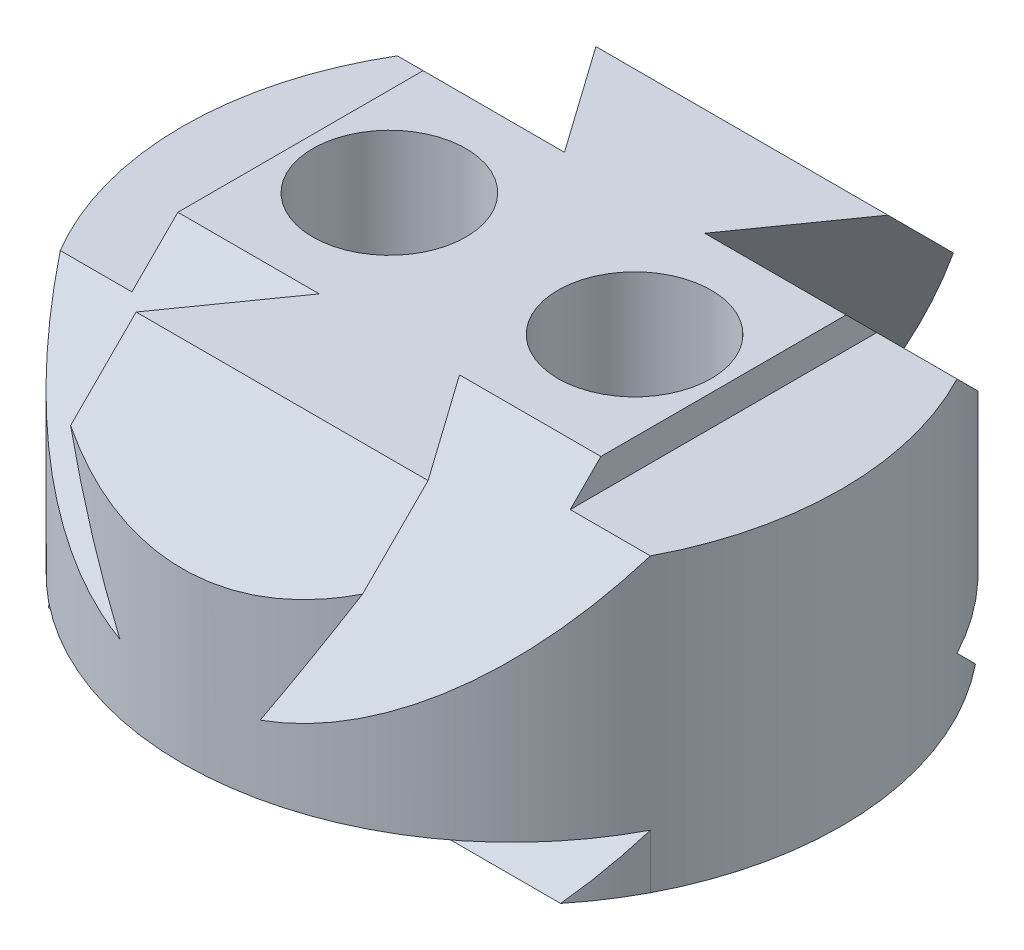
SolidWorks part; units mm, degrees
ref_plane "Front Plane" through (0, 0, 0) normal (0, 0, 1) x (1, 0, 0)
ref_plane "Top Plane" through (0, 0, 0) normal (0, 1, 0) x (1, 0, 0)
ref_plane "Right Plane" through (0, 0, 0) normal (1, 0, 0) x (0, 0, -1)
sketch "Sketch1" plane through (0, 0, 0) normal (0, 1, 0) x (1, 0, 0)
  circle A0 centre (0, 0) radius 21.5
  dimension "D1" = 43
extrude "Boss-Extrude1" add sketch "Sketch1" against normal blind 4
sketch "Sketch2" plane through (0, 0, 0) normal (0, 1, 0) x (1, 0, 0)
  circle A0 centre (0, 0) radius 5.875
  dimension "D1" = 11.75
extrude "Boss-Extrude2" add sketch "Sketch2" along normal blind 65
sketch "Sketch3" plane through (0, 0, 0) normal (0, 1, 0) x (1, 0, 0)
  line L0 (0, 0) -> (0, 21.5) construction
  line L1 (0, 21.5) -> (0, -21.5) construction
  circle A0 centre (0, 0) radius 21.5 construction
ref_plane "Plane1" through (0, 15.5, 0) normal (0, 1, 0) x (1, 0, 0)
sketch "Sketch5" plane through (0, 0, 0) normal (1, 0, 0) x (0, 0, -1)
  line L4 (21.5, 0) -> (-21.5, 0) construction
  line L5 (6, 0) -> (0, 0) construction
  line L8 (21.5, 0) -> (0, 0)
  line L10 (-21.5, 0) -> (0, 0)
  line L11 (21.5, 0) -> (6, 15.5)
  line L12 (23.65, 15.5) -> (-23.65, 15.5) construction
  line L13 (6, 15.5) -> (-6, 15.5)
  line L14 (-6, 15.5) -> (-21.5, 0)
  dimension "D1" = 21.5
  dimension "D2" = 15.5
  dimension "D3" = 15.5
extrude "Boss-Extrude3" add sketch "Sketch5" along normal up to surface and the other way up to surface up to face at (0, -4, 21.5) other way up to face at (0, -4, 21.5)
ref_plane "Plane2" through (0, 4.75, -4.75) normal (0, 0.7071, -0.7071) x (-1, 0, 0)
ref_plane "Plane3" through (0, 4.75, 4.75) normal (0, -0.7071, -0.7071) x (-1, 0, 0)
sketch "Sketch6" plane through (0, 4.75, 4.75) normal (0, -0.7071, -0.7071) x (-1, 0, 0)
  line L0 (0, 15.2028) -> (4.5753, 15.2028)
  line L1 (20.6458, 15.2028) -> (-20.6458, 15.2028) construction
  line L2 (4.5753, 15.2028) -> (9.525, 20.1525)
  line L3 (9.525, 20.1525) -> (0, 20.1525)
  line L4 (0, 20.1525) -> (-9.525, 20.1525)
  line L5 (-9.525, 20.1525) -> (-4.5753, 15.2028)
  line L6 (-4.5753, 15.2028) -> (0, 15.2028)
  dimension "D1" = 7
  dimension "D2" = 45
  dimension "D3" = 45
  dimension "D4" = 9.525
ref_plane "Plane4" through (0, 0, 6) normal (0, 0, 1) x (1, 0, 0)
ref_plane "Plane5" through (0, 0, -6) normal (0, 0, 1) x (1, 0, 0)
sketch "Sketch10" plane through (0, 4.75, -4.75) normal (0, 0.7071, -0.7071) x (-1, 0, 0)
  line L14 (0, 15.2028) -> (-4.5753, 15.2028)
  line L15 (20.6458, 15.2028) -> (-20.6458, 15.2028) construction
  line L16 (-4.5753, 15.2028) -> (-9.525, 20.1525)
  line L18 (9.525, 20.1525) -> (4.5753, 15.2028)
  line L19 (4.5753, 15.2028) -> (0, 15.2028)
  line L20 (9.525, 20.1525) -> (0, 20.1525)
  line L21 (0, 20.1525) -> (-9.525, 20.1525)
  dimension "D1" = 45
  dimension "D2" = 9.525
  dimension "D3" = 7
  dimension "D4" = 45
sketch "Sketch11" plane through (0, 0, 6) normal (0, 0, 1) x (1, 0, 0)
  line L0 (0, 65) -> (0, 15.5) construction
  line L1 (5.875, 65) -> (-5.875, 65) construction
  line L2 (0, 65) -> (0, 15.5) construction
sketch "Sketch12" plane through (0, 15.5, 0) normal (0, 1, 0) x (1, 0, 0)
  line L0 (-20.6458, 6) -> (20.6458, 6)
  line L1 (20.6458, -6) -> (-20.6458, -6)
  arc A0 (-20.6458, 6) -> (-20.6458, -6) centre (0, 0) ccw
  arc A2 (20.6458, 6) -> (20.6458, -6) centre (0, 0) cw
extrude "Boss-Extrude12" add sketch "Sketch6" along normal up to surface (21.9203 mm away) contours L3 L4 L5 L6 L0 L2
sketch "Sketch14" plane through (0, 15.5, 0) normal (0, 1, 0) x (1, 0, 0)
  circle A0 centre (0, 0) radius 5.875
  dimension "D1" = 11.75
ref_plane "Plane7" through (0, -4, 0) normal (0, -1, 0) x (-1, 0, 0)
sketch "Sketch17" plane through (0, 0, 0) normal (0, 0, 1) x (1, 0, 0)
  line L1 (-23.65, -4) -> (23.65, -4) construction
  line L2 (0, -4) -> (5, -4)
  line L3 (0, -4) -> (0, 6)
  line L4 (0, 6) -> (5, -4)
extrude "Boss-Extrude13" add sketch "Sketch10" against normal up to surface (13.8239 mm away) contours L21 L16 L14 L19 L18 L20
extrude "Cut-Extrude3" cut sketch "Sketch14" along normal blind 10 and the other way blind 2 flip side to cut contours A0
ref_plane "Plane8" through (0, 13.5, 0) normal (0, 1, 0) x (1, 0, 0)
sketch "Sketch18" plane through (0, 0, 0) normal (1, 0, 0) x (0, 0, -1)
  line L0 (0, -4) -> (21.5, -4)
  line L1 (-23.65, -4) -> (23.65, -4) construction
  line L2 (21.5, -4) -> (21.5, 7) construction
  line L3 (21.5, -4) -> (0, -49)
  line L4 (0, -49) -> (0, -4)
  dimension "D1" = 45
sketch "Sketch19" plane through (0, 13.5, 0) normal (0, 1, 0) x (1, 0, 0)
  line L0 (0, 0) -> (11, 0) construction
  line L1 (0, 21.5) -> (0, -21.5) construction
  line L2 (11, 0) -> (11, 8)
  line L3 (19.9562, 8) -> (4.5753, 8) construction
  line L4 (11, 0) -> (11, -8)
  line L5 (4.5753, -8) -> (19.9562, -8) construction
  line L6 (0, 0) -> (-11, 0) construction
  line L7 (-11, 0) -> (-11, 8)
  line L8 (-4.5753, 8) -> (-19.9562, 8) construction
  line L9 (-11, 0) -> (-11, -8)
  line L10 (-19.9562, -8) -> (-4.5753, -8) construction
sketch "Sketch20" plane through (0, 0, 0) normal (0, 0, 1) x (1, 0, 0)
  line L0 (0, 13.5) -> (0, 25.5)
  line L1 (0, 13.5) -> (-11, 13.5) construction
  line L2 (0, 13.5) -> (11, 13.5) construction
  line L3 (0, 65) -> (0, 15.5) construction
  line L4 (0, 25.5) -> (-11, 13.5)
  line L5 (0, 25.5) -> (11, 13.5)
  line L6 (-5.875, 65) -> (-5.875, 13.5) construction
  line L7 (5.875, 13.5) -> (5.875, 65) construction
  line L8 (11, 13.5) -> (21.5, 2.0455)
  line L9 (21.5, -4) -> (21.5, 13.5) construction
  point P11 (-5.875, 19.0909)
  point P15 (5.875, 19.0909)
ref_plane "Plane9" through (0, 13.5, 0) normal (-0.6757, -0.7372, 0) x (0, 0, 1)
ref_plane "Plane10" through (0, 13.5, 0) normal (0.6757, -0.7372, 0) x (0, 0, -1)
ref_plane "Plane11" through (6.8269, 7.4475, 0) normal (-0.6757, -0.7372, 0) x (0, 0, 1)
sketch "Sketch22" plane through (6.8269, 7.4475, 0) normal (-0.6757, -0.7372, 0) x (0, 0, 1)
  line L0 (0, 17.231) -> (15, 17.231)
  line L1 (15, 17.231) -> (15, 27.3886)
  line L2 (15, 27.3886) -> (-15, 27.3886)
  line L3 (-15, 27.3886) -> (-15, 17.231)
  line L4 (-15, 17.231) -> (0, 17.231)
ref_plane "Plane12" through (-6.8269, 7.4475, 0) normal (0.6757, -0.7372, 0) x (-0.7372, -0.6757, 0)
sketch "Sketch23" plane through (-6.8269, 7.4475, 0) normal (0.6757, -0.7372, 0) x (-0.7372, -0.6757, 0)
  line L0 (-17.231, 0) -> (-17.231, 15)
  line L1 (-17.231, 15) -> (-27.231, 15)
  line L2 (-27.231, 15) -> (-27.231, -15)
  line L3 (-27.231, -15) -> (-17.231, -15)
  line L4 (-17.231, -15) -> (-17.231, 0)
sketch "Sketch24" plane through (0, 0, 0) normal (0, 0, 1) x (1, 0, 0)
  line L0 (0, -4) -> (10, -4)
  line L1 (0, -4) -> (0, -49) construction
  line L2 (0, -49) -> (0, -4) construction
  line L3 (-23.65, -4) -> (23.65, -4) construction
  line L4 (10, -4) -> (13.5355, -7.5355)
  line L6 (0, -4) -> (-10, -4)
  line L7 (-10, -4) -> (-13.5355, -7.5355)
  line L8 (-13.5355, -7.5355) -> (13.5355, -7.5355)
  dimension "D1" = 10
  dimension "D2" = 10
  dimension "D3" = 5
  dimension "D4" = 45
  dimension "D5" = 5
sketch "Sketch29" plane through (0, 65, 0) normal (0, 1, 0) x (1, 0, 0)
  circle A0 centre (0, 0) radius 7.5081
  dimension "D1" = 15.0162
extrude "Cut-Extrude9" cut sketch "Sketch29" along direction (0, 1, 0) on the side against the normal up to surface (51.5 mm away)
sketch "Sketch30" plane through (0, 13.5, 0) normal (0, 1, 0) x (1, 0, 0)
  line L0 (-23.65, 0) -> (23.65, 0) construction
  circle A0 centre (-8, 0) radius 5
  circle A1 centre (8, 0) radius 5
  dimension "D1" = 10
  dimension "D2" = 10
  dimension "D3" = 8
  dimension "D4" = 8
extrude "Cut-Extrude10" cut sketch "Sketch30" against normal blind 9.8
sketch "Sketch31" plane through (0, 0, -6) normal (0, 0, 1) x (1, 0, 0)
  line L0 (-19.9562, 13.5) -> (-21.5, 13.5) construction
  line L1 (21.5, 13.5) -> (13.8, 13.5)
  line L2 (21.5, 13.5) -> (21.5, 11.5)
  line L3 (21.5, 11.5) -> (13.8, 11.5)
  line L4 (13.8, 13.5) -> (13.8, 11.5)
  line L5 (-21.5, 13.5) -> (-13.8, 13.5)
  line L6 (-21.5, 13.5) -> (-21.5, 10.5)
  line L7 (-21.5, 10.5) -> (-13.8, 10.5)
  line L8 (-13.8, 13.5) -> (-13.8, 10.5)
  dimension "D1" = 7.7
  dimension "D2" = 2
  dimension "D3" = 7.7
  dimension "D4" = 3
extrude "Cut-Extrude13" cut sketch "Sketch31" against normal through all both and the other way through all
sketch "Sketch32" plane through (0, 13.5, 0) normal (0, 1, 0) x (1, 0, 0)
  line L1 (-1.3, 8) -> (1.3, 8)
  line L2 (-1.3, 8) -> (-1.3, -8)
  line L3 (-1.3, -8) -> (1.3, -8)
  line L4 (1.3, 8) -> (1.3, -8)
  line L5 (-1.3, 8) -> (1.3, -8) construction
  line L6 (-1.3, -8) -> (1.3, 8) construction
  point P0 (0, 0)
  dimension "D1" = 16
  dimension "D2" = 2.6
sketch "Sketch33" plane through (0, -4, 0) normal (0, -1, 0) x (1, 0, 0)
  line L0 (0, 0) -> (0, 10)
  line L1 (0, -21.5) -> (0, 21.5) construction
  line L2 (0, 0) -> (0, -10)
  line L3 (0, 0) -> (0, -21.5) construction
  dimension "D1" = 10
  dimension "D2" = 10
sketch "Sketch34" plane through (0, 0, 0) normal (1, 0, 0) x (0, 0, -1)
  line L0 (0, -4) -> (-10, -4)
  line L1 (0, -4) -> (-10, -4) construction
  line L2 (0, -4) -> (10, -4)
  line L3 (0, -4) -> (21.5, -4) construction
  line L4 (-10, -4) -> (-13.5355, -7.5355)
  line L5 (10, -4) -> (13.5355, -7.5355)
  line L6 (-13.5355, -7.5355) -> (13.5355, -7.5355)
  dimension "D1" = 10
  dimension "D2" = 5
  dimension "D3" = 5
  dimension "D4" = 135
  dimension "D5" = 135
extrude "Boss-Extrude14" add sketch "Sketch34" along normal up to surface and the other way up to surface up to face at (0.0768, 6.0018, 0) other way up to face at (0.0768, 6.0018, 0)
sketch "Sketch35" plane through (0, -7.5355, 0) normal (0, -1, 0) x (1, 0, 0)
  circle A0 centre (-8.3844, 0) radius 5.284
  circle A1 centre (10.939, 0) radius 5.1632
sketch "Sketch36" plane through (0, -7.5355, 0) normal (0, -1, 0) x (1, 0, 0)
  circle A0 centre (-8, 0) radius 5
  circle A1 centre (8, 0) radius 5
  dimension "D1" = 10
  dimension "D2" = 10
  dimension "D3" = 8
  dimension "D4" = 8
extrude "Cut-Extrude14" cut sketch "Sketch36" against normal blind 3
sketch "Sketch38" plane through (0, -4.5355, 0) normal (0, -1, 0) x (1, 0, 0)
  circle A0 centre (-8, 0) radius 1.8923
  circle A1 centre (8, 0) radius 1.8923
  dimension "D1" = 3.7846
  dimension "D2" = 3.7846
extrude "Cut-Extrude15" cut sketch "Sketch38" against normal up to next
